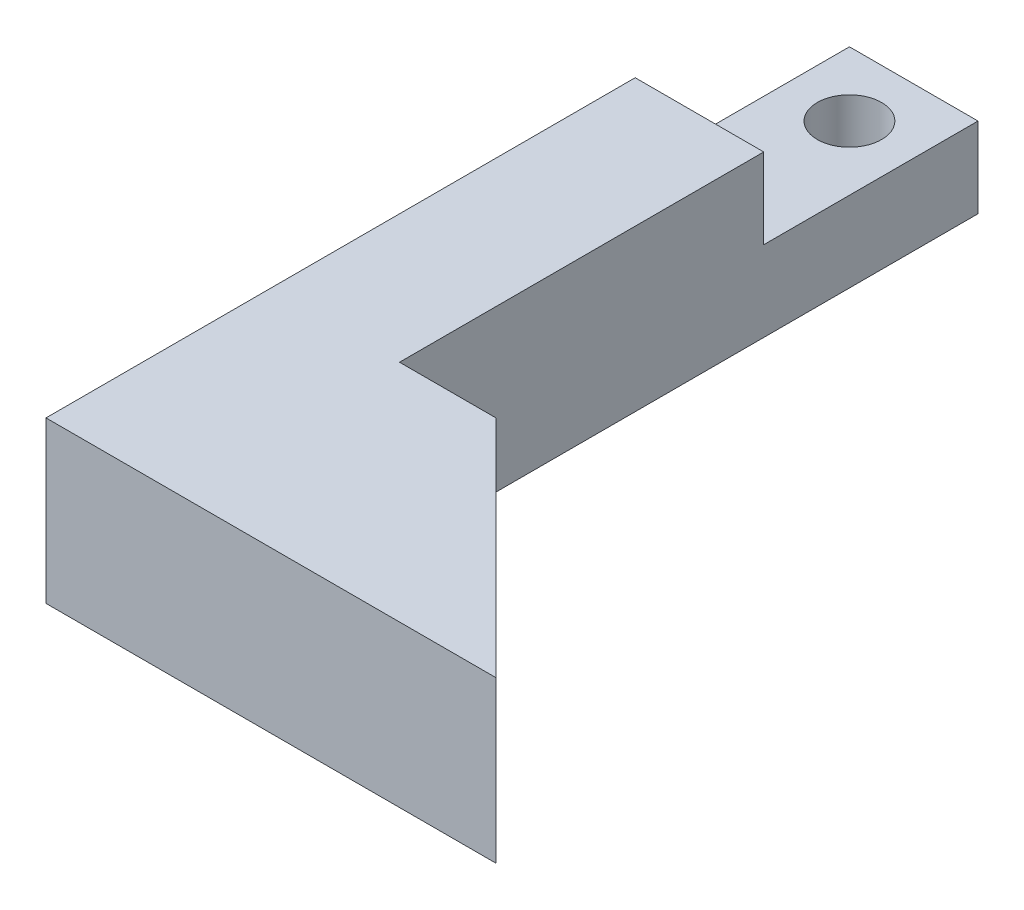
SolidWorks part; units mm, degrees
material "PE High Density"
ref_plane "Front Plane" through (0, 0, 0) normal (0, 0, 1) x (1, 0, 0)
ref_plane "Top Plane" through (0, 0, 0) normal (0, 1, 0) x (1, 0, 0)
ref_plane "Right Plane" through (0, 0, 0) normal (1, 0, 0) x (0, 0, -1)
sketch "Sketch1" plane through (0, 0, 0) normal (0, 1, 0) x (1, 0, 0)
  line L0 (50, -77.5999) -> (120, -147.5999)
  line L1 (-20, 102.4001) -> (20, 102.4001)
  line L2 (-20, 102.4001) -> (-20, -147.5999)
  line L3 (-20, -147.5999) -> (50, -147.5999)
  line L5 (120, -147.5999) -> (50, -147.5999)
  line L7 (20, -77.5999) -> (50, -77.5999)
  line L8 (20, -77.5999) -> (20, 102.4001)
  point P0 (0, 0)
  dimension "D1" = 250
  dimension "D2" = 70
  dimension "D4" = 40
  dimension "D5" = 70
extrude "Boss-Extrude1" add sketch "Sketch1" along normal blind 50
sketch "Sketch2" plane through (0, 50, 0) normal (0, 1, 0) x (1, 0, 0)
  line L0 (20, 102.4001) -> (-20, 102.4001) construction
  circle A0 centre (0, 82.4001) radius 10
  dimension "D1" = 20
  dimension "D2" = 20
extrude "Cut-Extrude1" cut sketch "Sketch2" against normal blind 77
scale "Scale1" scale about centroid uniform scaling yes scale factor 0.75
sketch "Sketch4" plane through (0, 43.75, 0) normal (0, 1, 0) x (1, 0, 0)
  line L0 (19.4459, -72.1225) -> (19.4459, 62.8775) construction
  line L1 (-10.5541, 62.8775) -> (19.4459, 62.8775)
  line L2 (-10.5541, 62.8775) -> (-10.5541, 12.8775)
  line L3 (-10.5541, 12.8775) -> (19.4459, 12.8775)
  line L4 (19.4459, 62.8775) -> (19.4459, 12.8775)
  dimension "D1" = 50
extrude "Cut-Extrude2" cut sketch "Sketch4" against normal blind 18.75
